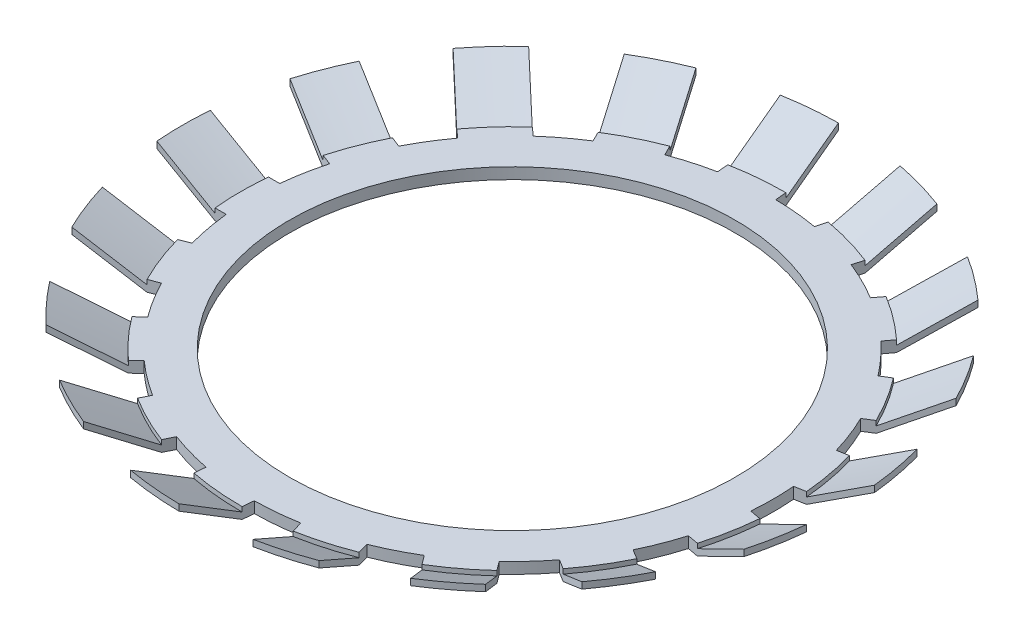
SolidWorks part; units mm, degrees
ref_plane "Front Plane" through (0, 0, 0) normal (0, 0, 1) x (1, 0, 0)
ref_plane "Top Plane" through (0, 0, 0) normal (0, 1, 0) x (1, 0, 0)
ref_plane "Right Plane" through (0, 0, 0) normal (1, 0, 0) x (0, 0, -1)
sketch "Sketch1" plane through (0, 0, 0) normal (0, 1, 0) x (1, 0, 0)
  circle A0 centre (0, 0) radius 25
  circle A1 centre (0, 0) radius 30.5
  dimension "D1" = 50
  dimension "D2" = 61
extrude "Boss-Extrude1" add sketch "Sketch1" along normal blind 1.25
sketch "Sketch2" plane through (0, 0, 0) normal (0, 1, 0) x (1, 0, 0)
  circle A0 centre (0, 0) radius 30.5 construction
  circle A1 centre (0, 0) radius 30.5
extrude "Boss-Extrude2" add sketch "Sketch2" along normal blind 30 draft 60 draft outward yes
sketch "Sketch3" plane through (0, 0, 0) normal (0, -1, 0) x (1, 0, 0)
  circle A0 centre (0, 0) radius 29.25
  circle A1 centre (0, 0) radius 30.5
  circle A2 centre (0, 0) radius 30.5
  dimension "D1" = 0
  dimension "D2" = 1.25
extrude "Cut-Extrude1" cut sketch "Sketch3" against normal blind 30 draft 60 contours A0 draft outward yes
sketch "Sketch4" plane through (0, 0, 0) normal (0, 1, 0) x (1, 0, 0)
  circle A0 centre (0, 0) radius 37
  circle A1 centre (0, 0) radius 94.6747
  dimension "D1" = 74
extrude "Cut-Extrude2" cut sketch "Sketch4" along normal blind 30
sketch "Sketch7" plane through (0, 0, 0) normal (0, 1, 0) x (1, 0, 0)
  circle A0 centre (0, 0) radius 25
  circle A1 centre (0, 0) radius 30.5
  dimension "D1" = 50
  dimension "D2" = 61
extrude "Boss-Extrude4" add sketch "Sketch7" along normal blind 1.25 contours A1 | A0
sketch "Sketch5" plane through (0, 0, 0) normal (0, 1, 0) x (1, 0, 0)
  line L0 (-29.0957, -3) -> (-36.8782, -3)
  line L1 (-36.8782, -3) -> (-36.8782, 3)
  line L2 (-36.8782, 3) -> (-29.0957, 3)
  line L3 (-35.4716, 10.5245) -> (-33.3042, 16.1194)
  line L4 (-33.3042, 16.1194) -> (-26.0473, 13.308)
  line L5 (-28.2147, 7.7132) -> (-35.4716, 10.5245)
  line L6 (-29.2744, 22.6276) -> (-25.2322, 27.0617)
  line L7 (-25.2322, 27.0617) -> (-19.4809, 21.8187)
  line L8 (-23.5231, 17.3847) -> (-29.2744, 22.6276)
  line L9 (-19.1235, 31.6748) -> (-13.7525, 34.3492)
  line L10 (-13.7525, 34.3492) -> (-10.2836, 27.3827)
  line L11 (-15.6546, 24.7082) -> (-19.1235, 31.6748)
  line L12 (-6.3899, 36.4441) -> (-0.4155, 36.9977)
  line L13 (-0.4155, 36.9977) -> (0.3026, 29.2484)
  line L14 (-5.6718, 28.6948) -> (-6.3899, 36.4441)
  line L15 (7.2067, 36.2914) -> (12.9777, 34.6494)
  line L16 (12.9777, 34.6494) -> (10.8479, 27.164)
  line L17 (5.077, 28.806) -> (7.2067, 36.2914)
  line L18 (19.83, 31.2373) -> (24.6181, 27.6215)
  line L19 (24.6181, 27.6215) -> (19.9282, 21.411)
  line L20 (15.1401, 25.0268) -> (19.83, 31.2373)
  line L21 (29.7752, 21.9645) -> (32.9338, 16.8632)
  line L22 (32.9338, 16.8632) -> (26.317, 12.7663)
  line L23 (23.1584, 17.8676) -> (29.7752, 21.9645)
  line L24 (35.699, 9.7253) -> (36.8015, 3.8274)
  line L25 (36.8015, 3.8274) -> (29.1516, 2.3974)
  line L26 (28.0491, 8.2952) -> (35.699, 9.7253)
  line L27 (36.8015, -3.8274) -> (35.699, -9.7253)
  line L28 (35.699, -9.7253) -> (28.0491, -8.2952)
  line L29 (29.1516, -2.3974) -> (36.8015, -3.8274)
  line L30 (32.9338, -16.8632) -> (29.7752, -21.9645)
  line L31 (29.7752, -21.9645) -> (23.1584, -17.8676)
  line L32 (26.317, -12.7663) -> (32.9338, -16.8632)
  line L33 (24.6181, -27.6215) -> (19.83, -31.2373)
  line L34 (19.83, -31.2373) -> (15.1401, -25.0268)
  line L35 (19.9282, -21.411) -> (24.6181, -27.6215)
  line L36 (12.9777, -34.6494) -> (7.2067, -36.2914)
  line L37 (7.2067, -36.2914) -> (5.077, -28.806)
  line L38 (10.8479, -27.164) -> (12.9777, -34.6494)
  line L39 (-0.4155, -36.9977) -> (-6.3899, -36.4441)
  line L40 (-6.3899, -36.4441) -> (-5.6718, -28.6948)
  line L41 (0.3026, -29.2484) -> (-0.4155, -36.9977)
  line L42 (-13.7525, -34.3492) -> (-19.1235, -31.6748)
  line L43 (-19.1235, -31.6748) -> (-15.6546, -24.7082)
  line L44 (-10.2836, -27.3827) -> (-13.7525, -34.3492)
  line L45 (-25.2322, -27.0617) -> (-29.2744, -22.6276)
  line L46 (-29.2744, -22.6276) -> (-23.5231, -17.3847)
  line L47 (-19.4809, -21.8187) -> (-25.2322, -27.0617)
  line L48 (-33.3042, -16.1194) -> (-35.4716, -10.5245)
  line L49 (-35.4716, -10.5245) -> (-28.2147, -7.7132)
  line L50 (-26.0473, -13.308) -> (-33.3042, -16.1194)
  line L51 (-29.0957, 3) -> (-29.0957, -3)
  circle A0 centre (0, 0) radius 29.25 construction
  circle A1 centre (0, 0) radius 37 construction
  circle A2 centre (0, 0) radius 29.25
  circle A3 centre (0, 0) radius 37
  point P6 (-36.8782, 0)
  point P9 (-29.0957, 0)
  point P77 (0, 0)
  dimension "D1" = 6
  dimension "D2" = 17
extrude "Cut-Extrude3" cut sketch "Sketch5" along normal blind 30 contours L5 A3 L2 A2 | L8 A3 L4 A2 | L11 A3 L7 A2 | L14 A3 L10 A2 | L17 A3 L13 A2 | L20 A3 L16 A2 | L23 A3 L19 A2 | L26 A3 L22 A2 | L29 A3 L25 A2 | L32 A3 L28 A2 | L35 A3 L31 A2 | L38 A3 L34 A2 | L41 A3 L37 A2 | L44 A3 L40 A2 | L0 A3 L49 A2 | L50 A3 L46 A2 | L47 A3 L43 A2
